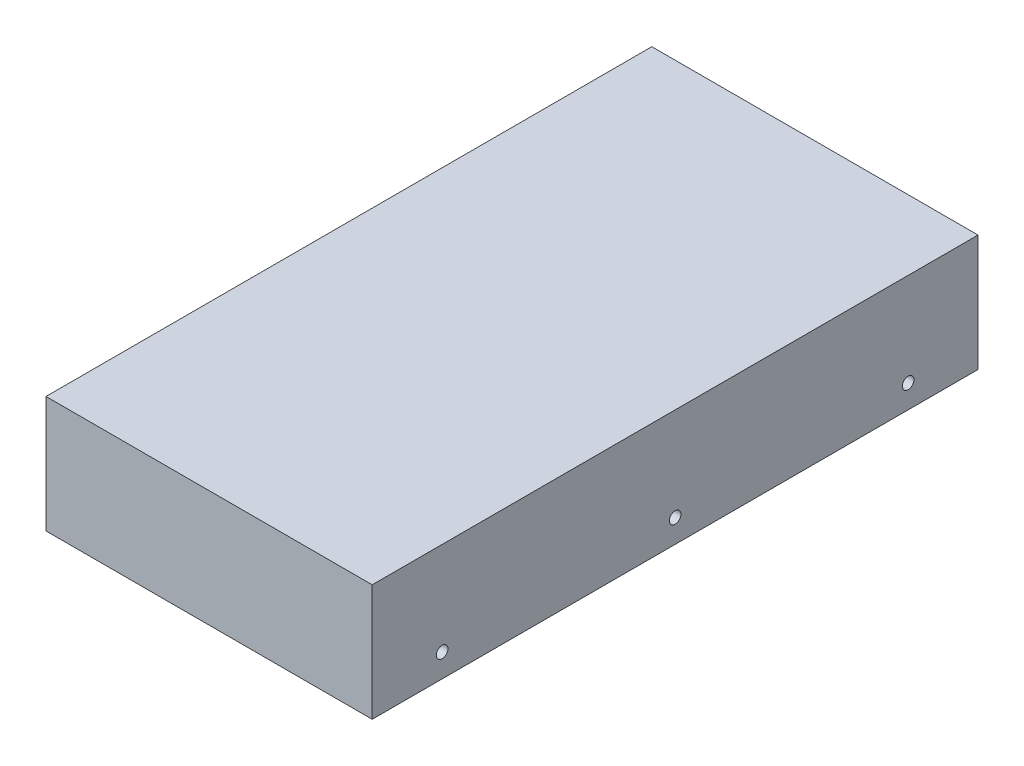
SolidWorks part; units mm, degrees
ref_plane "Front Plane" through (0, 0, 0) normal (0, 0, 1) x (1, 0, 0)
ref_plane "Top Plane" through (0, 0, 0) normal (0, 1, 0) x (1, 0, 0)
ref_plane "Right Plane" through (0, 0, 0) normal (1, 0, 0) x (0, 0, -1)
sketch "Sketch2" plane through (0, 0, 0) normal (1, 0, 0) x (0, 0, -1)
  line L0 (0, 101.6) -> (0, -25.4) construction
  line L1 (-330.2, -25.4) -> (330.2, -25.4)
  line L2 (-330.2, -25.4) -> (-330.2, 101.6)
  line L3 (-330.2, 101.6) -> (330.2, 101.6)
  line L4 (330.2, -25.4) -> (330.2, 101.6)
  line L5 (-254, 0) -> (254, 0) construction
  circle A0 centre (0, 0) radius 6.35
  circle A1 centre (-254, 0) radius 6.35
  circle A2 centre (254, 0) radius 6.35
  point P13 (0, 0)
  dimension "D4" = 12.7
  dimension "D1" = 660.4
  dimension "D2" = 127
  dimension "D3" = 25.4
  dimension "D5" = 508
extrude "Boss-Extrude1" add sketch "Sketch2" along normal mid plane 355.6
